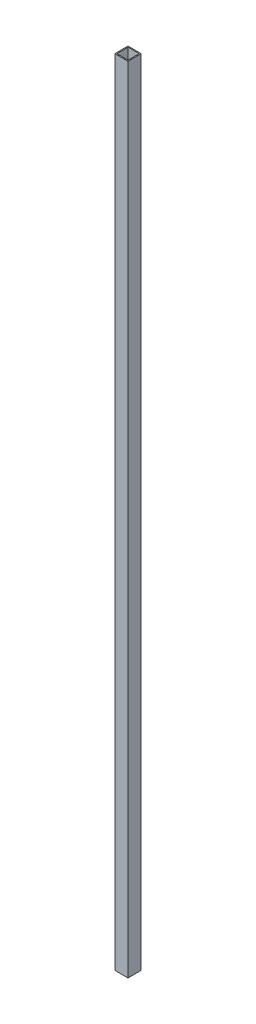
SolidWorks part; units mm, degrees
material "Alloy Steel"
ref_plane "Front Plane" through (0, 0, 0) normal (0, 0, 1) x (1, 0, 0)
ref_plane "Top Plane" through (0, 0, 0) normal (0, 1, 0) x (1, 0, 0)
ref_plane "Right Plane" through (0, 0, 0) normal (1, 0, 0) x (0, 0, -1)
sketch "Sketch1" plane through (0, 0, 0) normal (0, 1, 0) x (1, 0, 0)
  line L0 (-10.795, 10.795) -> (10.795, 10.795)
  line L1 (-12.7, -12.7) -> (12.7, -12.7)
  line L2 (-12.7, -12.7) -> (-12.7, 12.7)
  line L3 (-12.7, 12.7) -> (12.7, 12.7)
  line L4 (12.7, -12.7) -> (12.7, 12.7)
  line L5 (-12.7, -12.7) -> (12.7, 12.7) construction
  line L6 (-12.7, 12.7) -> (12.7, -12.7) construction
  line L7 (10.795, -10.795) -> (10.795, 10.795)
  line L8 (-10.795, -10.795) -> (10.795, -10.795)
  line L9 (-10.795, -10.795) -> (-10.795, 10.795)
  point P0 (0, 0)
  dimension "D1" = 25.4
  dimension "D2" = 1.905
extrude "Boss-Extrude1" add sketch "Sketch1" along normal mid plane 1524
